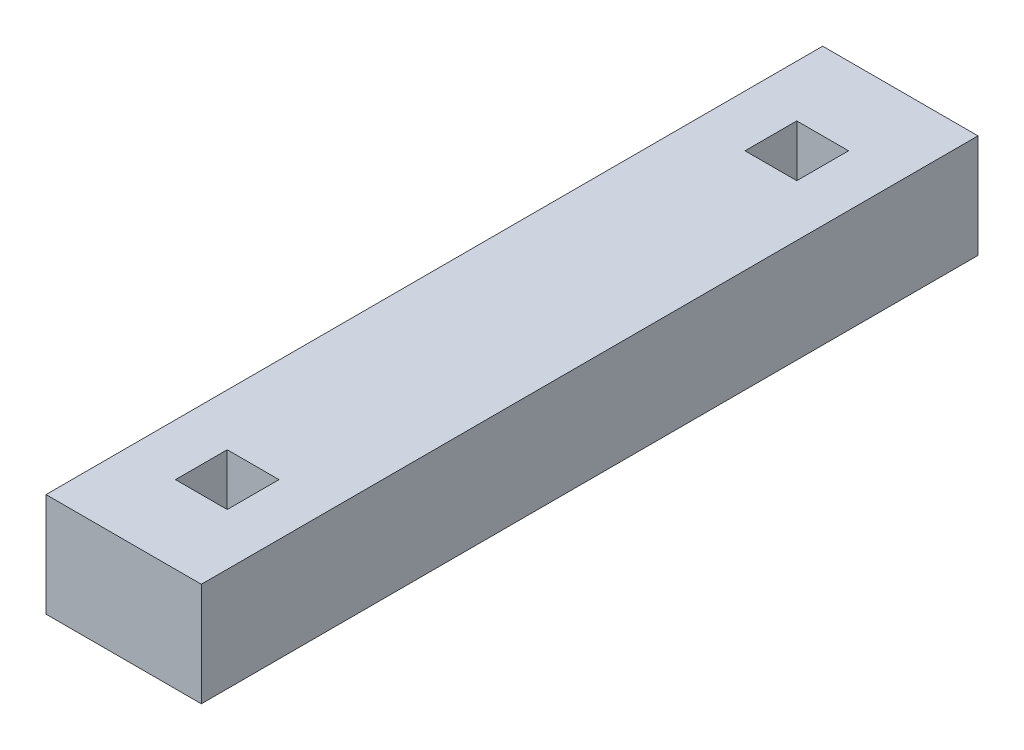
SolidWorks part; units mm, degrees
ref_plane "Front Plane" through (0, 0, 0) normal (0, 0, 1) x (1, 0, 0)
ref_plane "Top Plane" through (0, 0, 0) normal (0, 1, 0) x (1, 0, 0)
ref_plane "Right Plane" through (0, 0, 0) normal (1, 0, 0) x (0, 0, -1)
sketch "Sketch1" plane through (0, 0, 0) normal (0, 1, 0) x (1, 0, 0)
  line L0 (0, 70) -> (0, -80) construction
  line L1 (-15, 70) -> (15, 70)
  line L2 (-15, 70) -> (-15, -80)
  line L3 (-15, -80) -> (15, -80)
  line L4 (15, 70) -> (15, -80)
  line L5 (-5, 55) -> (5, 55)
  line L6 (-5, 55) -> (-5, 45)
  line L7 (-5, 45) -> (5, 45)
  line L8 (5, 55) -> (5, 45)
  line L9 (15, -5) -> (-15, -5) construction
  line L10 (-5, -65) -> (-5, -55)
  line L11 (-5, -55) -> (5, -55)
  line L12 (5, -65) -> (5, -55)
  line L13 (-5, -65) -> (5, -65)
  point P9 (0, 55)
  point P10 (0, 70)
  dimension "D3" = 10
  dimension "D5" = 100
  dimension "D4" = 10
  dimension "D1" = 30
  dimension "D2" = 150
extrude "Boss-Extrude1" add sketch "Sketch1" along normal blind 20
